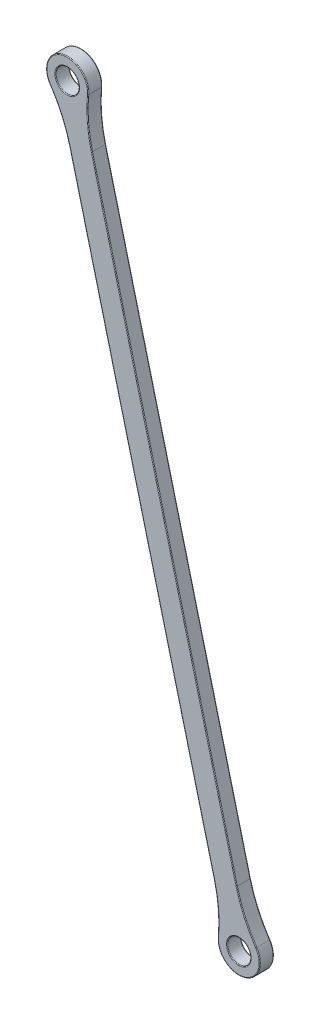
SolidWorks part; units mm, degrees
material "AISI 1020"
ref_plane "Front Plane" through (0, 0, 0) normal (0, 0, 1) x (1, 0, 0)
ref_plane "Top Plane" through (0, 0, 0) normal (0, 1, 0) x (1, 0, 0)
ref_plane "Right Plane" through (0, 0, 0) normal (1, 0, 0) x (0, 0, -1)
sketch "Sketch1" plane through (0, 0, 0) normal (0, 0, 1) x (1, 0, 0)
  line L0 (14.5, 81.5) -> (-22.3206, 224.8466) construction
  line L1 (14.5, 81.5) -> (-22.3206, 224.8466) construction
  line L2 (-22.3206, 224.8466) -> (14.5, 81.5) construction
  line L3 (-19.8992, 225.4686) -> (16.9214, 82.122)
  line L4 (-24.742, 224.2246) -> (12.0786, 80.878)
  circle A0 centre (-22.3206, 224.8466) radius 4.5 construction
  circle A1 centre (14.5, 81.5) radius 4.5 construction
  arc A2 (-19.8992, 225.4686) -> (-24.742, 224.2246) centre (-22.3206, 224.8466) ccw
  arc A3 (12.0786, 80.878) -> (16.9214, 82.122) centre (14.5, 81.5) ccw
  arc A4 (-24.742, 224.2246) -> (-19.8992, 225.4686) centre (-22.3206, 224.8466) ccw
  arc A5 (16.9214, 82.122) -> (12.0786, 80.878) centre (14.5, 81.5) ccw
  arc A6 (15.9905, 85.746) -> (11.1477, 84.502) centre (14.5, 81.5) cw
  arc A7 (-18.9683, 221.8445) -> (-23.8111, 220.6006) centre (-22.3206, 224.8466) ccw
  point P5 (-3.9103, 153.1733)
  dimension "D1" = 9
  dimension "D2" = 5
extrude "Boss-Extrude1" add sketch "Sketch1" along normal blind 3 contours A5 L3 A4 L4 | L3 A7 L4 A2 | A6 L3 A3 L4
fillet "Fillet1" radius 30 4 edges at (15.9905, 85.746, 1.5) (11.1477, 84.502, 1.5) (-23.8111, 220.6006, 1.5) (-18.9683, 221.8445, 1.5)
fillet "Fillet2" radius 0.15 20 edges at (-19.8206, 224.8466, 3) (-19.8206, 224.8466, 0) (17, 81.5, 3) (17, 81.5, 0) (-23.557, 217.8507, 3) (-23.557, 217.8507, 0) (-6.3317, 152.5513, 0) (-6.3317, 152.5513, 3) (10.0452, 87.034, 3) (10.0452, 87.034, 0) (15.6195, 77.1415, 0) (15.6195, 77.1415, 3) (15.7364, 88.4959, 3) (15.7364, 88.4959, 0) (-1.4889, 153.7953, 3) (-1.4889, 153.7953, 0) (-17.8657, 219.3126, 3) (-17.8657, 219.3126, 0) (-23.4401, 229.2051, 0) (-23.4401, 229.2051, 3)
